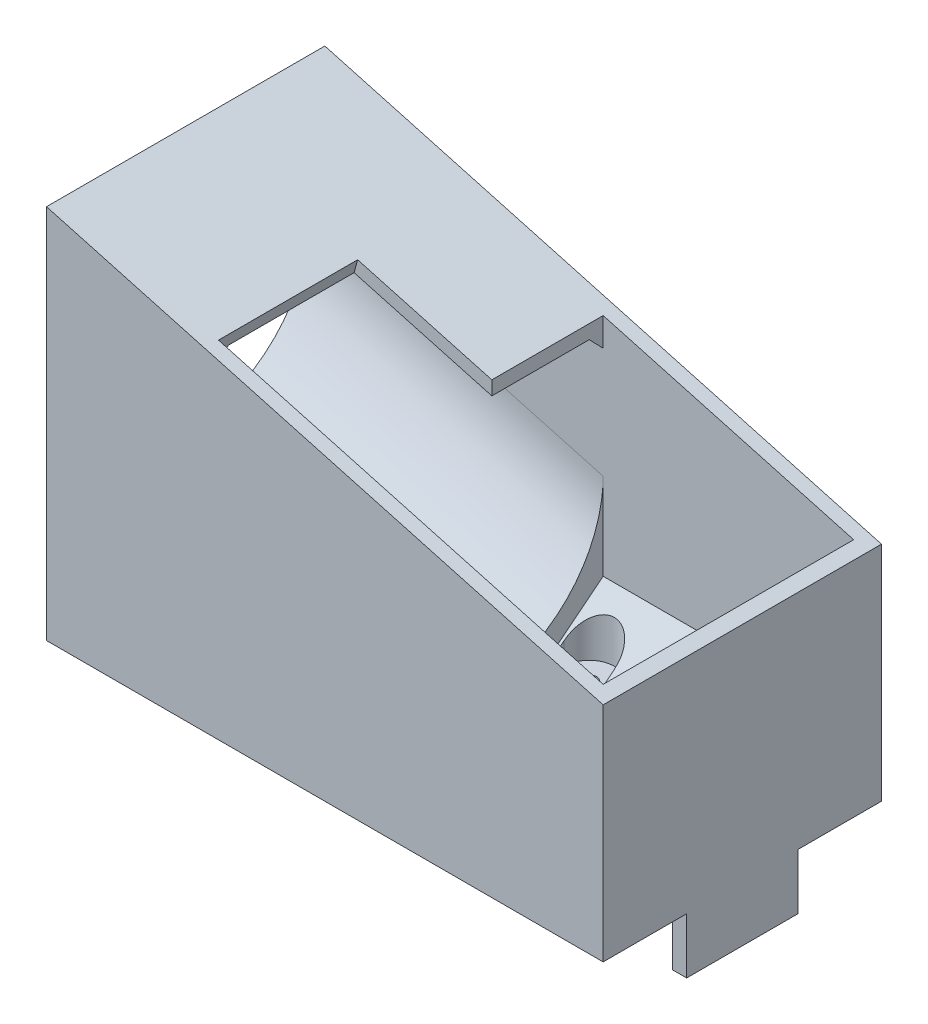
SolidWorks part; units mm, degrees
ref_plane "前视基准面" through (0, 0, 0) normal (0, 0, 1) x (1, 0, 0)
ref_plane "上视基准面" through (0, 0, 0) normal (0, 1, 0) x (1, 0, 0)
ref_plane "右视基准面" through (0, 0, 0) normal (1, 0, 0) x (0, 0, -1)
sketch "草图1" plane through (0, 0, 0) normal (0, 0, 1) x (1, 0, 0)
  line L0 (0, 0) -> (0, -20)
  line L1 (0, -20) -> (100, -20)
  line L2 (100, -20) -> (100, 0)
  line L3 (100, 0) -> (100, 100)
  line L4 (100, 100) -> (-100, 155)
  line L5 (-100, 155) -> (-100, 0)
  line L6 (-100, 0) -> (0, 0)
  line L7 (100, 0) -> (-100, 55)
  dimension "D1" = 100
  dimension "D2" = 100
  dimension "D3" = 100
  dimension "D4" = 20
  dimension "D5" = 20
  dimension "D6" = 155
extrude "凸台-拉伸1" add sketch "草图1" along normal blind 100 contours L7 L3 L4 L5 | L2 L7 L5 L6 L0 L1
sketch "草图2" plane through (0, -20, 0) normal (0, -1, 0) x (1, 0, 0)
  line L0 (0, 100) -> (0, 0) construction
  line L1 (5, 70) -> (95, 70)
  line L2 (5, 70) -> (5, 30)
  line L3 (5, 30) -> (95, 30)
  line L4 (95, 70) -> (95, 30)
  line L5 (0, 100) -> (100, 100) construction
  dimension "D1" = 90
  dimension "D2" = 5
  dimension "D3" = 40
  dimension "D4" = 30
extrude "切除-拉伸1" cut sketch "草图2" against normal through all
sketch "草图3" plane through (-100, 0, 0) normal (-1, 0, 0) x (0, 0, 1)
  line L0 (100, 155) -> (100, 0) construction
  line L1 (100, 155) -> (0, 155) construction
  circle A0 centre (50, 105) radius 45
  dimension "D3" = 90
  dimension "D1" = 50
  dimension "D2" = 50
sketch "草图4" plane through (0, 0, 0) normal (0, 0, -1) x (-1, 0, 0)
  line L0 (100, 105) -> (-59.6804, 61.0879)
  line L3 (100, 60) -> (100, 150) construction
sweep "切除-扫描1" cut profiles "草图3" path "草图4"
sketch "草图5" plane through (32.5973, 118.5357, 0) normal (0.2652, 0.9642, 0) x (0.9642, -0.2652, 0)
  line L0 (-28.6218, -45) -> (-5.9205, -45)
  line L1 (69.9049, 0) -> (-137.5198, 0) construction
  line L2 (-5.9205, -45) -> (-5.9205, -70)
  line L3 (-28.6218, -45) -> (-78.6218, -45)
  line L4 (-78.6218, -95) -> (-78.6218, -45)
  line L5 (64.7193, -70) -> (-28.6218, -70) construction
  line L6 (-78.6218, -95) -> (-5.9205, -95)
  line L8 (-5.9205, -95) -> (-5.9205, -70)
  dimension "D1" = 50
  dimension "D2" = 50
  dimension "D3" = 45
extrude "切除-拉伸2" cut sketch "草图5" against normal blind 20
sketch "草图6" plane through (0, -20, 0) normal (0, -1, 0) x (1, 0, 0)
  line L1 (100, 100) -> (0, 100)
  line L2 (100, 100) -> (100, 0)
  line L3 (100, 0) -> (0, 0)
  line L4 (0, 100) -> (0, 0)
extrude "切除-拉伸3" cut sketch "草图6" against normal blind 20
ref_plane "基准面1" through (0, 25, 0) normal (0, 1, 0) x (1, 0, 0)
sketch "草图7" plane through (0, 25, 0) normal (0, 1, 0) x (1, 0, 0)
  line L0 (-100, 0) -> (100, 0) construction
  line L1 (5, -95) -> (95, -95)
  line L2 (5, -95) -> (5, -5)
  line L3 (5, -5) -> (95, -5)
  line L4 (95, -95) -> (95, -5)
  line L6 (100, 0) -> (100, -100) construction
  dimension "D1" = 90
  dimension "D2" = 90
  dimension "D3" = 5
  dimension "D4" = 5
extrude "切除-拉伸4" cut sketch "草图7" along normal through all
sketch "草图8" plane through (0, 25, 0) normal (0, 1, 0) x (1, 0, 0)
  line L0 (5, -70) -> (5, -95) construction
  line L1 (95, -95) -> (95, -70) construction
  line L3 (95, -70) -> (59.6804, -70) construction
  circle A0 centre (15, -80) radius 2.6
  circle A1 centre (85, -80) radius 2.6
  circle A2 centre (15, -20) radius 2.6
  circle A3 centre (85, -20) radius 2.6
  dimension "D1" = 5.2
  dimension "D2" = 5.2
  dimension "D3" = 10
  dimension "D4" = 10
  dimension "D5" = 10
  dimension "D6" = 10
  dimension "D7" = 2
extrude "切除-拉伸5" cut sketch "草图8" against normal blind 20
sketch "草图9" plane through (-100, 0, 0) normal (-1, 0, 0) x (0, 0, 1)
  line L0 (100, 155) -> (0, 155) construction
  line L1 (5, 150) -> (95, 150)
  line L2 (5, 150) -> (5, 105)
  line L3 (5, 105) -> (95, 105)
  line L4 (95, 150) -> (95, 105)
  line L5 (0, 155) -> (0, 0) construction
  dimension "D1" = 45
  dimension "D2" = 90
  dimension "D3" = 5
  dimension "5" = 5
sketch "草图10" plane through (0, 0, 0) normal (0, 0, -1) x (-1, 0, 0)
  line L0 (100, 105) -> (-53.3272, 62.835)
  line L1 (100, 150) -> (100, 105) construction
sweep "切除-扫描2" cut profiles "草图9" path "草图10"
chamfer "倒角1" distance 5 angle 45 2 edges at (-72.2443, 142.3672, 95) (-47.5, 135.5625, 5)
sketch "草图11" plane through (100, 0, 0) normal (1, 0, 0) x (0, 0, -1)
  line L0 (-5, 25) -> (-5, 45)
  line L1 (55, 25) -> (-55, 25) construction
  line L2 (-5, 45) -> (-30, 25)
  line L3 (-30, 25) -> (-5, 25)
  line L4 (-70, 25) -> (-95, 45)
  line L5 (-95, 45) -> (-95, 25)
  line L6 (-95, 25) -> (-70, 25)
  line L7 (-100, 0) -> (-100, 100) construction
  line L8 (0, 0) -> (0, 100) construction
  dimension "D1" = 20
  dimension "D2" = 25
  dimension "D3" = 95
  dimension "D4" = 95
  dimension "D5" = 25
  dimension "D6" = 20
extrude "凸台-拉伸2" add sketch "草图11" against normal blind 100
sketch "草图12" plane through (0, 25, 0) normal (0, 1, 0) x (1, 0, 0)
  line L0 (95, -30) -> (59.6804, -30) construction
  line L2 (6, -20) -> (24, -20)
  line L3 (6, -20) -> (6, -33.9979)
  line L4 (6, -33.9979) -> (24, -33.9979)
  line L5 (24, -20) -> (24, -33.9979)
  line L6 (76, -20) -> (94.6849, -20)
  line L7 (76, -20) -> (76, -33.9979)
  line L8 (76, -33.9979) -> (94.6849, -33.9979)
  line L9 (94.6849, -20) -> (94.6849, -33.9979)
  line L11 (24, -80) -> (6, -80)
  line L12 (24, -80) -> (24, -64.4658)
  line L13 (24, -64.4658) -> (6, -64.4658)
  line L14 (6, -80) -> (6, -64.4658)
  line L15 (76, -80) -> (94, -80)
  line L16 (76, -80) -> (76, -65.7187)
  line L17 (76, -65.7187) -> (94, -65.7187)
  line L18 (94, -80) -> (94, -65.7187)
  circle A0 centre (15, -20) radius 9
  circle A1 centre (85, -20) radius 9
  circle A2 centre (85, -20) radius 2.6 construction
  circle A3 centre (15, -80) radius 9
  circle A4 centre (15, -20) radius 2.6 construction
  circle A5 centre (85, -80) radius 9
  dimension "D1" = 18
  dimension "D2" = 18
  dimension "D5" = 0
  dimension "D6" = 0
  dimension "D3" = 10
  dimension "D4" = 10
  dimension "D7" = 2
extrude "切除-拉伸6" cut sketch "草图12" along normal blind 130 contours L2 A0 | A0 L3 L4 L5 | L2 A0 | L6 A1 | L6 A1 | A1 L7 L8 L9 L6 | A3 L12 L13 L14 | L11 A3 | L11 A3 | A5 L18 L17 L16 | L15 A5 | L15 A5
sketch "草图13" plane through (-100, 0, 0) normal (-1, 0, 0) x (0, 0, 1)
  line L1 (100, 0) -> (0, 0) construction
  line L2 (-4.9765, 20) -> (-4.9765, -2.9956)
  line L3 (-4.9765, -2.9956) -> (106.6812, -2.9956)
  line L4 (106.6812, 20) -> (106.6812, -2.9956)
  line L5 (-4.9765, 20) -> (106.6812, 20)
  dimension "D1" = 20
extrude "切除-拉伸7" cut sketch "草图13" against normal blind 100
sketch "草图14" plane through (100, 0, 0) normal (1, 0, 0) x (0, 0, -1)
  line L1 (-30, 20) -> (11.7913, 20)
  line L2 (-30, 20) -> (-30, -3.6238)
  line L3 (-30, -3.6238) -> (11.7913, -3.6238)
  line L4 (11.7913, 20) -> (11.7913, -3.6238)
  line L5 (-100, 0) -> (-100, 100) construction
  line L6 (-111.641, 20) -> (-70, 20)
  line L7 (-70, 20) -> (-70, -3.1298)
  line L8 (-70, -3.1298) -> (-111.641, -3.1298)
  line L9 (-111.641, 20) -> (-111.641, -3.1298)
  line L10 (0, 0) -> (0, 100) construction
  line L12 (0, 0) -> (-100, 0) construction
  dimension "D1" = 30
  dimension "D2" = 30
  dimension "D3" = 20
extrude "切除-拉伸8" cut sketch "草图14" against normal blind 100
